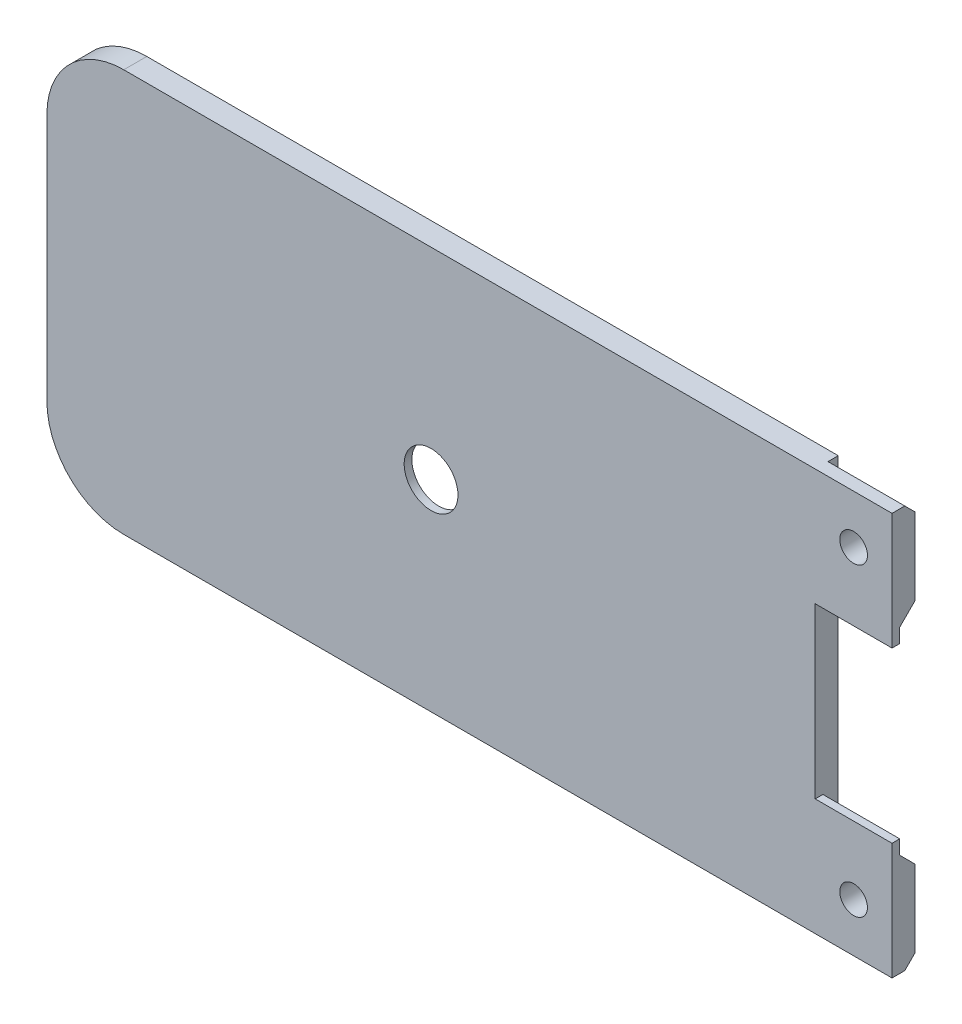
SolidWorks part; units mm, degrees
ref_plane "Plano frontal" through (0, 0, 0) normal (0, 0, 1) x (1, 0, 0)
ref_plane "Plano superior" through (0, 0, 0) normal (0, 1, 0) x (1, 0, 0)
ref_plane "Plano direito" through (0, 0, 0) normal (1, 0, 0) x (0, 0, -1)
sketch "Esboço1" plane through (0, 0, 0) normal (0, 0, 1) x (1, 0, 0)
  line L0 (55, 0) -> (-55, 0) construction
  line L1 (50, -26.19) -> (-50, -26.19)
  line L2 (50, -26.19) -> (50, 26.19)
  line L3 (50, 26.19) -> (-50, 26.19)
  line L4 (-50, -26.19) -> (-50, 26.19)
  line L5 (50, -26.19) -> (-50, 26.19) construction
  line L6 (50, 26.19) -> (-50, -26.19) construction
  line L7 (50, 26.19) -> (60, 26.19)
  line L8 (50, 26.19) -> (50, 11)
  line L9 (50, 11) -> (60, 11)
  line L10 (60, 26.19) -> (60, 11)
  line L11 (50, -11) -> (60, -11)
  line L12 (60, -26.19) -> (60, -11)
  line L13 (50, -26.19) -> (60, -26.19)
  line L14 (50, -26.19) -> (50, -11)
  point P0 (0, 0)
  dimension "D1" = 22
  dimension "D2" = 52.38
  dimension "D3" = 100
  dimension "D4" = 10
extrude "Ressalto-extrusão1" add sketch "Esboço1" along normal blind 3 contours L2 L1 L4 L3 | L8 L7 L10 L9 | L14 L11 L12 L13
sketch "Esboço2" plane through (60, 0, 0) normal (1, 0, 0) x (0, 0, -1)
  line L0 (-2, -11) -> (-2, -12.85)
  line L1 (-3, -11) -> (0, -11) construction
  line L2 (-2, -12.85) -> (0, -14.85)
  line L3 (0, -26.19) -> (0, -11) construction
  line L4 (0, -14.85) -> (0, -24.85) construction
  line L5 (0, -24.85) -> (-1.34, -26.19)
  line L6 (-3, -26.19) -> (0, -26.19) construction
  line L7 (-1.34, -26.19) -> (0, -26.19)
  line L8 (0, -26.19) -> (0, -24.85)
  line L9 (-2, -11) -> (0, -11)
  line L10 (0, -11) -> (0, -14.85)
  line L12 (1.65, 0) -> (-1.65, 0) construction
  line L13 (0, 14.85) -> (0, 24.85) construction
  line L14 (0, 11) -> (0, 14.85)
  line L15 (-2, 11) -> (0, 11)
  line L16 (0, 26.19) -> (0, 24.85)
  line L17 (-1.34, 26.19) -> (0, 26.19)
  line L18 (0, 24.85) -> (-1.34, 26.19)
  line L19 (-2, 12.85) -> (0, 14.85)
  line L20 (-2, 11) -> (-2, 12.85)
  point P4 (0, -14.4742)
  dimension "D1" = 1.85
  dimension "D2" = 10
  dimension "D3" = 2
  dimension "D4" = 3.85
extrude "Corte-extrusão1" cut sketch "Esboço2" against normal up to surface (10 mm away) up to face at (50, 0, 1.5)
sketch "Esboço3" plane through (0, 0, 0) normal (0, 0, -1) x (-1, 0, 0)
  line L0 (-60, 24.85) -> (-60, 14.85) construction
  line L1 (-50, 24.85) -> (-60, 24.85) construction
  line L2 (1.65, 0) -> (-1.65, 0) construction
  circle A0 centre (-55, 19.85) radius 1.8
  circle A1 centre (-55, -19.85) radius 1.8
  point P4 (-60, 19.85)
  point P5 (0, 0)
  point P8 (-55, 24.85)
  dimension "D1" = 3.6
extrude "Corte-extrusão2" cut sketch "Esboço3" against normal through all
sketch "Esboço4" plane through (0, 0, 3) normal (0, 0, 1) x (1, 0, 0)
  circle A0 centre (0, 0) radius 3.5
  dimension "D1" = 7
extrude "Corte-extrusão3" cut sketch "Esboço4" against normal through all
sketch "Esboço5" plane through (0, 0, 0) normal (0, 0, -1) x (-1, 0, 0)
  circle A0 centre (0, 0) radius 6.5
  dimension "D1" = 13
extrude "Corte-extrusão4" cut sketch "Esboço5" against normal blind 2
fillet "Filete1" radius 10 2 edges at (-50, -26.19, 1.5) (-50, 26.19, 1.5)
